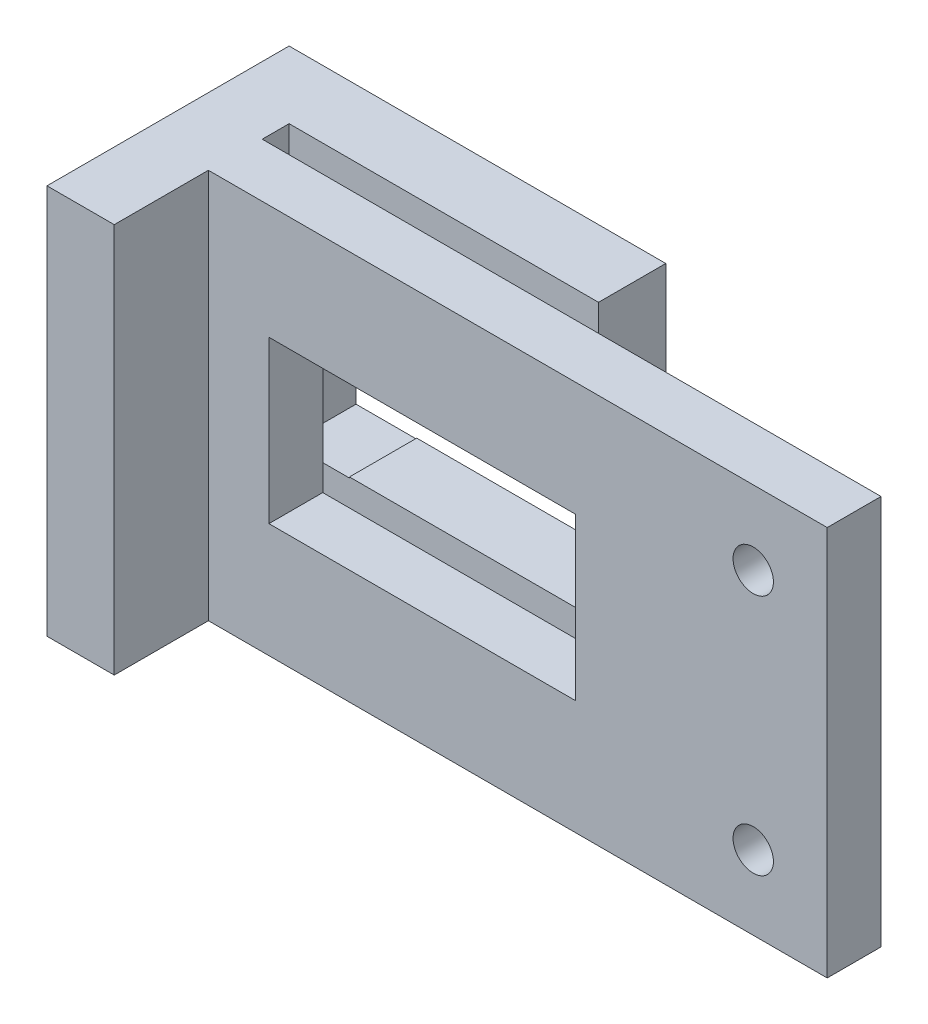
SolidWorks part; units mm, degrees
ref_plane "Alzado" through (0, 0, 0) normal (1, 0, 0) x (0, 1, 0)
ref_plane "Planta" through (0, 0, 0) normal (0, 0, 1) x (0, 1, 0)
ref_plane "Vista lateral" through (0, 0, 0) normal (0, 1, 0) x (-1, 0, 0)
sketch "Croquis1" plane through (0, 0, 0) normal (0, 0, 1) x (0, 1, 0)
  line L1 (-14.5, 23) -> (14.5, 23)
  line L2 (-14.5, 23) -> (-14.5, -23)
  line L3 (-14.5, -23) -> (14.5, -23)
  line L4 (14.5, 23) -> (14.5, -23)
  point P0 (0, 0)
extrude "Saliente-Extruir1" add sketch "Croquis1" along normal blind 4
sketch "Croquis2" plane through (0, 0, 4) normal (0, 0, 1) x (1, 0, 0)
  line L1 (-23, 14.5) -> (-28, 14.5)
  line L2 (-23, 14.5) -> (-23, -14.5)
  line L3 (-23, -14.5) -> (-28, -14.5)
  line L4 (-28, 14.5) -> (-28, -14.5)
extrude "Saliente-Extruir2" add sketch "Croquis2" along normal blind 7 separate body
sketch "Croquis3" plane through (0, 0, 4) normal (0, 0, -1) x (1, 0, 0)
  line L1 (-28, 14.5) -> (-23, 14.5)
  line L2 (-28, 14.5) -> (-28, -14.5)
  line L3 (-28, -14.5) -> (-23, -14.5)
  line L4 (-23, 14.5) -> (-23, -14.5)
extrude "Saliente-Extruir3" add sketch "Croquis3" along normal blind 21
sketch "Croquis4" plane through (-28, 0, 0) normal (-1, 0, 0) x (0, -1, 0)
  line L0 (14.5, -17) -> (14.5, 11) construction
  line L1 (-14.5, -17) -> (14.5, -17)
  line L2 (-14.5, -17) -> (-14.5, -2)
  line L3 (-14.5, -2) -> (14.5, -2)
  line L4 (14.5, -17) -> (14.5, -2)
extrude "Saliente-Extruir4" add sketch "Croquis4" against normal blind 28
sketch "Croquis5" plane through (0, 0, 4) normal (0, 0, 1) x (1, 0, 0)
  line L3 (-18.5, 0) -> (-18.5, -6)
  line L8 (-18.5, -6) -> (4.3, -6)
  line L9 (-18.5, 0) -> (-18.5, 6)
  line L10 (4.3, -6) -> (4.3, 6)
  line L11 (4.3, 6) -> (-18.5, 6)
  circle A0 centre (17.5, -9) radius 1.5
  circle A1 centre (17.5, 9) radius 1.5
extrude "Cortar-Extruir1" cut sketch "Croquis5" against normal blind 28
sketch "Croquis6" plane through (0, 14.5, 0) normal (0, 1, 0) x (1, 0, 0)
  line L1 (-28, 17) -> (0, 17)
  line L2 (-28, 17) -> (-28, 7)
  line L4 (-28, 17) -> (-28, -11) construction
  line L5 (-28, 7) -> (0, 7)
  line L6 (0, 2) -> (0, 17) construction
  line L11 (0, 17) -> (0, 7)
extrude "Cortar-Extruir2" cut sketch "Croquis6" against normal blind 60
sketch "Croquis7" plane through (0, 0, 4) normal (0, 0, 1) x (1, 0, 0)
  line L9 (-18.5145, 5.9727) -> (-23.0251, 5.9727)
  line L10 (-18.5145, 5.9727) -> (-18.5145, -6.0706)
  line L11 (-18.5145, -6.0706) -> (-23.0251, -6.0706)
  line L12 (-23.0251, 5.9727) -> (-23.0251, -6.0706)
extrude "Cortar-Extruir3" cut sketch "Croquis7" against normal blind 60 from offset 5 offset against normal yes
sketch "Croquis8" plane through (0, 0, 4) normal (0, 0, 1) x (1, 0, 0)
  line L0 (4.3, 6) -> (-18.5, 6) construction
  line L1 (-20.2251, -6) -> (-16.7604, -6)
  line L2 (-20.2251, -6) -> (-20.2251, 6)
  line L3 (-20.2251, 6) -> (-16.7604, 6)
  line L4 (-16.7604, -6) -> (-16.7604, 6)
extrude "Cortar-Extruir4" cut sketch "Croquis8" against normal blind 60 from offset 5
